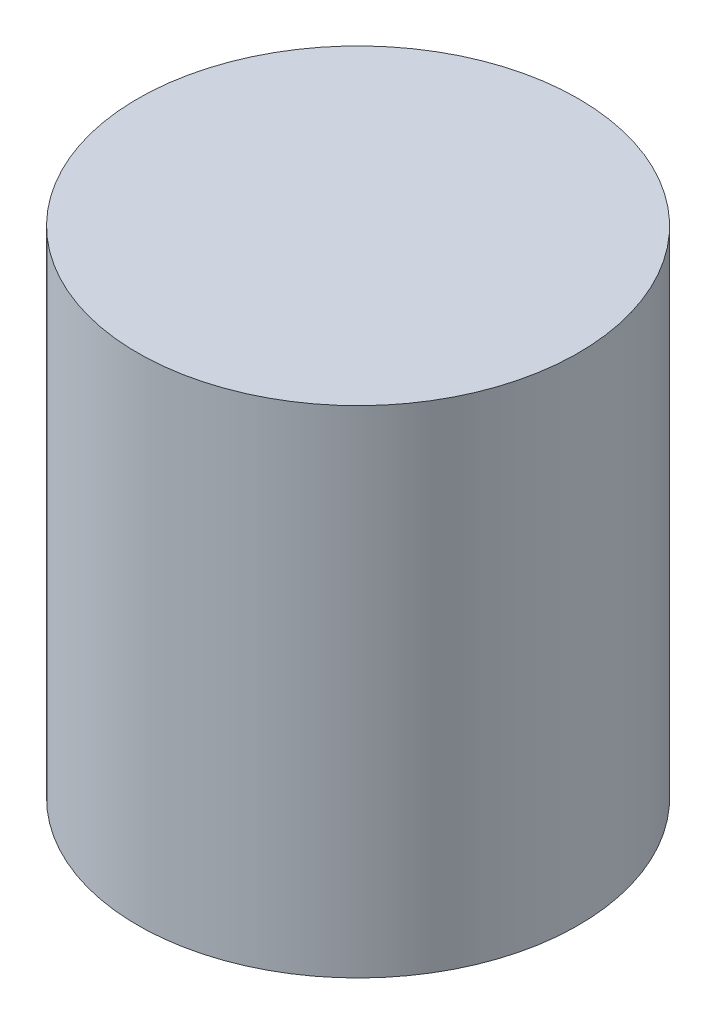
SolidWorks part; units mm, degrees
ref_plane "Plan de face" through (0, 0, 0) normal (0, 0, 1) x (1, 0, 0)
ref_plane "Plan de dessus" through (0, 0, 0) normal (0, 1, 0) x (1, 0, 0)
ref_plane "Plan de droite" through (0, 0, 0) normal (1, 0, 0) x (0, 0, -1)
sketch "Esquisse2" plane through (0, 0, 0) normal (0, 1, 0) x (1, 0, 0)
  circle A0 centre (0, 0) radius 40
extrude "Boss.-Extru.1" add sketch "Esquisse2" along normal blind 90
sketch "Esquisse3" plane through (0, 0, 0) normal (0, -1, 0) x (1, 0, 0)
  circle A0 centre (0, 0) radius 25
extrude "Enlèv. mat.-Extru.1" cut sketch "Esquisse3" against normal blind 70
